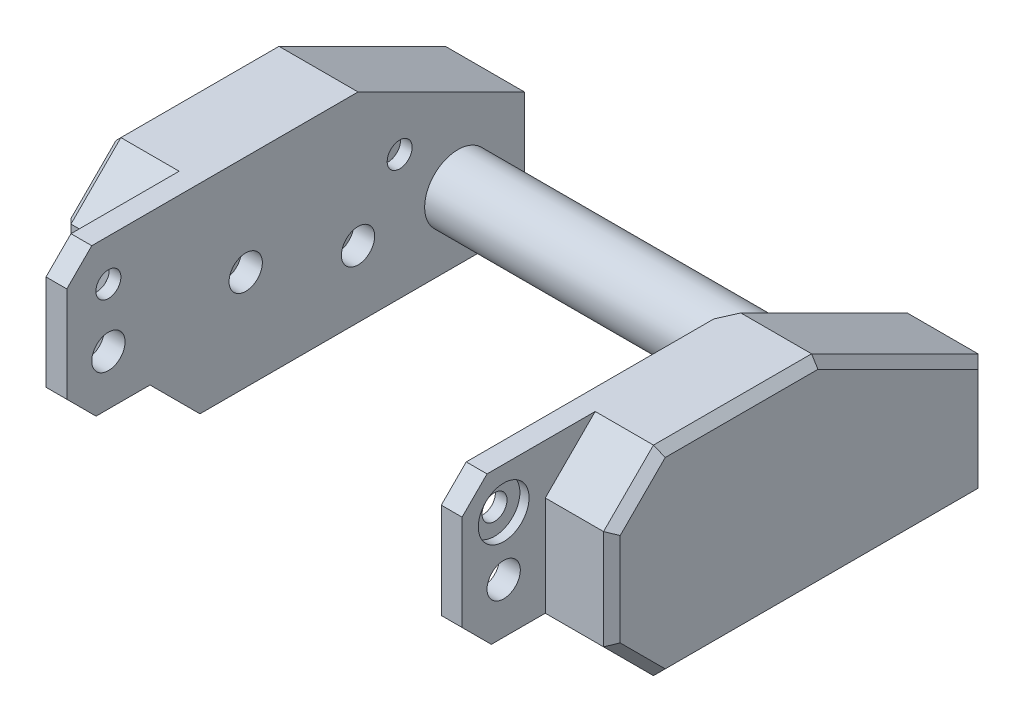
SolidWorks part; units mm, degrees
ref_plane "Front Plane" through (0, 0, 0) normal (0, 0, 1) x (1, 0, 0)
ref_plane "Top Plane" through (0, 0, 0) normal (0, 1, 0) x (1, 0, 0)
ref_plane "Right Plane" through (0, 0, 0) normal (1, 0, 0) x (0, 0, -1)
sketch "Sketch2" plane through (0, 0, 0) normal (1, 0, 0) x (0, 0, -1)
  line L1 (-22.5, -12) -> (22.5, -12)
  line L2 (-22.5, -12) -> (-22.5, 12)
  line L3 (-22.5, 12) -> (22.5, 12)
  line L4 (22.5, -12) -> (22.5, 12)
  line L5 (-22.5, -12) -> (22.5, 12) construction
  line L6 (-22.5, 12) -> (22.5, -12) construction
  point P0 (0, 0)
  dimension "D1" = 45
  dimension "D2" = 24
extrude "Boss-Extrude1" add sketch "Sketch2" along normal blind 50
sketch "Sketch14" plane through (50, 0, 0) normal (1, 0, 0) x (0, 0, -1)
  line L0 (2.5, 12) -> (22.5, 2)
  line L1 (22.5, 12) -> (-22.5, 12) construction
  line L2 (22.5, -12) -> (22.5, 12) construction
  line L5 (2.5, 12) -> (22.5, 12)
  line L6 (22.5, 12) -> (22.5, 2)
  dimension "D1" = 20
  dimension "D4" = 10
extrude "Cut-Extrude7" cut sketch "Sketch14" against normal up to surface (50 mm away) up to face at (0, 0, 0)
chamfer "Chamfer4" distance 6 angle 45 2 edges at (25, -12, 22.5) (25, 12, 22.5)
sketch "Sketch3" plane through (0, 0, -22.5) normal (0, 0, -1) x (-1, 0, 0)
  line L0 (0, 12) -> (-50, 12) construction
  line L1 (-47.5, -2) -> (-2.5, -2)
  line L2 (-47.5, -2) -> (-47.5, -12)
  line L3 (-47.5, -12) -> (-2.5, -12)
  line L4 (-2.5, -2) -> (-2.5, -12)
  line L5 (-50, -12) -> (0, -12) construction
  point P8 (-25, 12)
  point P9 (-25, -2)
  dimension "D1" = 45
  dimension "D3" = 10
extrude "Cut-Extrude1" cut sketch "Sketch3" against normal up to surface (45 mm away) up to face at (25, 0, 22.5)
sketch "Sketch4" plane through (2.5, 0, 0) normal (1, 0, 0) x (0, 0, -1)
  line L1 (22.5, -12) -> (22.5, 2) construction
  line L3 (-16.5, -12) -> (22.5, -12) construction
  circle A0 centre (14.5, -4) radius 2
  dimension "D1" = 8
  dimension "D2" = 8
  dimension "D3" = 4
extrude "Cut-Extrude2" cut sketch "Sketch4" along normal up to surface and the other way up to surface up to face at (50, 0.2857, 4.3571) other way up to face at (0, 0.2857, 4.3571)
sketch "Sketch8" plane through (0, 12, 0) normal (0, 1, 0) x (1, 0, 0)
  line L0 (0, 22.5) -> (50, 22.5) construction
  line L9 (2.5, 27.5) -> (47.5, 27.5)
  line L10 (2.5, 27.5) -> (2.5, -22.5)
  line L11 (2.5, -22.5) -> (47.5, -22.5)
  line L12 (47.5, 27.5) -> (47.5, -22.5)
  line L13 (50, -22.5) -> (0, -22.5) construction
  point P9 (25, 22.5)
  point P10 (25, 27.5)
  dimension "D1" = 45
  dimension "D3" = 50
extrude "Cut-Extrude4" cut sketch "Sketch8" against normal up to surface (14 mm away) up to face at (25, -2, -4.8333)
sketch "Sketch6" plane through (2.5, 0, 0) normal (1, 0, 0) x (0, 0, -1)
  circle A0 centre (14.5, -4) radius 4
  dimension "D1" = 8
extrude "Boss-Extrude2" add sketch "Sketch6" along normal up to surface (45 mm away)
sketch "Sketch7" plane through (0, 0, 0) normal (-1, 0, 0) x (0, 0, 1)
  line L0 (22.5, 6) -> (22.5, -6) construction
  line L1 (16.5, -12) -> (-22.5, -12) construction
  circle A0 centre (11, 0) radius 2
  dimension "D1" = 4
  dimension "D2" = 11.5
  dimension "D3" = 12
extrude "Cut-Extrude3" cut sketch "Sketch7" against normal up to surface (50 mm away)
sketch "Sketch13" plane through (47.5, 0, 0) normal (-1, 0, 0) x (0, 0, 1)
  line L0 (16.5, -12) -> (-22.5, -12) construction
  line L1 (-22.5, -12) -> (-22.5, 2) construction
  circle A0 centre (-2.5, -4) radius 2
  dimension "D3" = 4
  dimension "D1" = 8
  dimension "D2" = 20
extrude "Cut-Extrude6" cut sketch "Sketch13" along normal up to surface and the other way up to surface
sketch "Sketch29" plane through (0, 0, 0) normal (-1, 0, 0) x (0, 0, 1)
  line L0 (22.5, 6) -> (22.5, -6) construction
  line L1 (28.9853, 6) -> (22.5, 6)
  line L5 (22.5, -6) -> (28.9853, -6)
  line L6 (28.9853, -6) -> (32.5, -2.4853)
  line L7 (32.5, -2.4853) -> (32.5, 2.4853)
  line L8 (32.5, 2.4853) -> (28.9853, 6)
  line L9 (22.5, 6) -> (22.5, -6)
  line L11 (25.529, 7.5143) -> (21.4285, 3.4138) [skipped]
  line L12 (18.9857, -0.971) -> (21.036, -3.0213) [skipped]
  line L13 (20.5, 4.6268) -> (20.5, -1.1722) [skipped]
  arc A1 (22.5, -5.7446) -> (22.5, 5.7446) centre (26.5, 0) ccw construction
  dimension "D2" = 7
  dimension "D1" = 10
extrude "Boss-Extrude16" add sketch "Sketch29" against normal up to surface (50 mm away) up to face at (50, -4, -0.5)
sketch "Sketch30" plane through (0, 6, 0) normal (0, 1, 0) x (1, 0, 0)
  line L6 (50, -32.5) -> (0, -32.5) construction
  line L7 (2.5, -22.5) -> (47.5, -22.5)
  line L8 (2.5, -22.5) -> (2.5, -32.5)
  line L9 (2.5, -32.5) -> (47.5, -32.5)
  line L10 (47.5, -22.5) -> (47.5, -32.5)
  line L11 (47.5, -22.5) -> (47.5, -16.5) construction
  line L12 (2.5, 2.5) -> (2.5, -16.5) construction
  dimension "D1" = 22.5
extrude "Cut-Extrude13" cut sketch "Sketch30" against normal up to surface (12 mm away) up to face at (25, -6, 24.6618)
sketch "Sketch37" plane through (0, 0, 0) normal (-1, 0, 0) x (0, 0, 1)
  circle A0 centre (27.5, 0) radius 2
  dimension "D1" = 4
  dimension "D2" = 5
extrude "Cut-Extrude18" cut sketch "Sketch37" against normal up to surface (50 mm away)
sketch "Sketch43" plane through (50, 0, 0) normal (1, 0, 0) x (0, 0, -1)
  line L0 (22.5, -12) -> (22.5, 2) construction
  line L1 (-16.5, -12) -> (22.5, -12) construction
  circle A0 centre (7.5, 3) radius 1.5
  dimension "D1" = 15
  dimension "D2" = 3
  dimension "D3" = 15
extrude "Cut-Extrude20" cut sketch "Sketch43" against normal up to surface (50 mm away) up to face at (0, 0, 29.5)
sketch "Sketch44" plane through (50, 0, 0) normal (1, 0, 0) x (0, 0, -1)
  circle A0 centre (7.5, 3) radius 3.05
  dimension "D1" = 6.1
extrude "Cut-Extrude21" cut sketch "Sketch44" against normal blind 1.1
sketch "Sketch45" plane through (0, 0, 0) normal (-1, 0, 0) x (0, 0, 1)
  circle A0 centre (-7.5, 3) radius 3.05
  dimension "D1" = 6.1
extrude "Cut-Extrude22" cut sketch "Sketch45" against normal blind 1.1
sketch "Sketch48" plane through (50, 0, 0) normal (1, 0, 0) x (0, 0, -1)
  line L2 (-16.5, 12) -> (-22.5, 6)
  line L3 (-22.5, 6) -> (-28.9853, 6)
  line L4 (-28.9853, 6) -> (-32.5, 2.4853)
  line L5 (-32.5, 2.4853) -> (-32.5, 12)
  line L6 (-32.5, 12) -> (-16.5, 12)
extrude "Boss-Extrude23" add sketch "Sketch48" against normal up to surface (2.5 mm away) up to face at (47.5, 4.5, -7.5)
sketch "Sketch49" plane through (0, 0, 0) normal (-1, 0, 0) x (0, 0, 1)
  line L2 (28.9853, 6) -> (22.5, 6)
  line L3 (28.9853, 6) -> (22.5, 6) construction
  line L4 (22.5, 6) -> (16.5, 12) construction
  line L5 (22.5, 6) -> (16.5, 12)
  line L6 (16.5, 12) -> (32.5, 12)
  line L7 (32.5, 12) -> (32.5, 2.4853)
  line L8 (32.5, 2.4853) -> (28.9853, 6)
extrude "Boss-Extrude24" add sketch "Sketch49" against normal up to surface (2.5 mm away) up to face at (2.5, 1.5, -7.5)
sketch "Sketch55" plane through (0, 0, 0) normal (-1, 0, 0) x (0, 0, 1)
  line L0 (32.5, -2.4853) -> (32.5, 12) construction
  line L1 (-2.5, 12) -> (32.5, 12) construction
  circle A0 centre (27.5, 7) radius 3.05
  dimension "D1" = 5
  dimension "D2" = 5
  dimension "D3" = 6.1
extrude "Cut-Extrude28" cut sketch "Sketch55" against normal blind 1.1
sketch "Sketch57" plane through (0, 0, 0) normal (-1, 0, 0) x (0, 0, 1)
  circle A0 centre (27.5, 7) radius 1.5
  dimension "D1" = 3
extrude "Cut-Extrude29" cut sketch "Sketch57" against normal up to surface (50 mm away)
sketch "Sketch58" plane through (50, 0, 0) normal (1, 0, 0) x (0, 0, -1)
  circle A0 centre (-27.5, 7) radius 3.05
  dimension "D1" = 6.1
extrude "Cut-Extrude30" cut sketch "Sketch58" against normal blind 1.1
chamfer "Chamfer11" distance 3 angle 45 2 edges at (48.75, 12, 32.5) (1.25, 12, 32.5)
sketch "Sketch38" plane through (0, 0, 0) normal (-1, 0, 0) x (0, 0, 1)
  line L0 (-2.5, 12) -> (-22.5, 2)
  line L1 (-22.5, 2) -> (-22.5, -12)
  line L2 (-22.5, -12) -> (16.5, -12)
  line L3 (16.5, -12) -> (22.5, -6)
  line L4 (22.5, -6) -> (22.5, 6)
  line L6 (16.5, 12) -> (-2.5, 12)
  line L7 (16.5, 12) -> (22.5, 6)
  dimension "D1" = 12
extrude "Boss-Extrude19" add sketch "Sketch38" along normal blind 8
sketch "Sketch39" plane through (50, 0, 0) normal (1, 0, 0) x (0, 0, -1)
  line L0 (-22.5, 6) -> (-22.5, -6)
  line L1 (-22.5, -6) -> (-16.5, -12)
  line L2 (-16.5, -12) -> (22.5, -12)
  line L3 (22.5, -12) -> (22.5, 2)
  line L4 (22.5, 2) -> (2.5, 12)
  line L5 (2.5, 12) -> (-16.5, 12)
  line L6 (-16.5, 12) -> (-22.5, 6)
  dimension "D1" = 12
extrude "Boss-Extrude20" add sketch "Sketch39" along normal blind 8
chamfer "Chamfer7" distance 1 angle 45 14 edges at (58, 12, 7) (58, 7, -12.5) (58, -5, -22.5) (58, -12, -3) (58, -9, 19.5) (58, 0, 22.5) (58, 9, 19.5) (-8, 9, 19.5) (-8, 0, 22.5) (-8, -9, 19.5) (-8, -12, -3) (-8, -5, -22.5) (-8, 7, -12.5) (-8, 12, 7)
chamfer "Chamfer8" distance 1 angle 45 4 edges at (47.5, 7, -12.5) (47.5, -9, 19.5) (47.5, -12, -3) (47.5, -5, -22.5)
chamfer "Chamfer9" [suppressed] distance 1 angle 45
